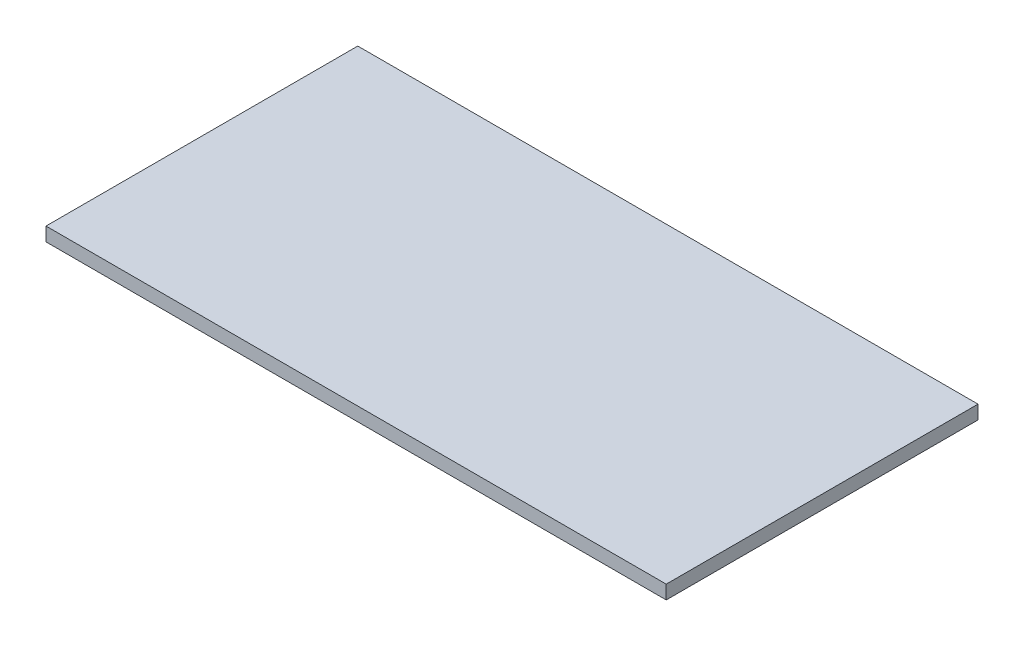
SolidWorks part; units mm, degrees
material "Oak"
ref_plane "Front Plane" through (0, 0, 0) normal (0, 0, 1) x (1, 0, 0)
ref_plane "Top Plane" through (0, 0, 0) normal (0, 1, 0) x (1, 0, 0)
ref_plane "Right Plane" through (0, 0, 0) normal (1, 0, 0) x (0, 0, -1)
sketch "Sketch1" plane through (0, 0, 0) normal (0, 1, 0) x (1, 0, 0)
  line L1 (0, 0) -> (1492, 0)
  line L2 (0, 0) -> (0, 750)
  line L3 (0, 750) -> (1492, 750)
  line L4 (1492, 0) -> (1492, 750)
  dimension "D1" = 1492
  dimension "D2" = 750
extrude "Boss-Extrude1" add sketch "Sketch1" along normal blind 33
